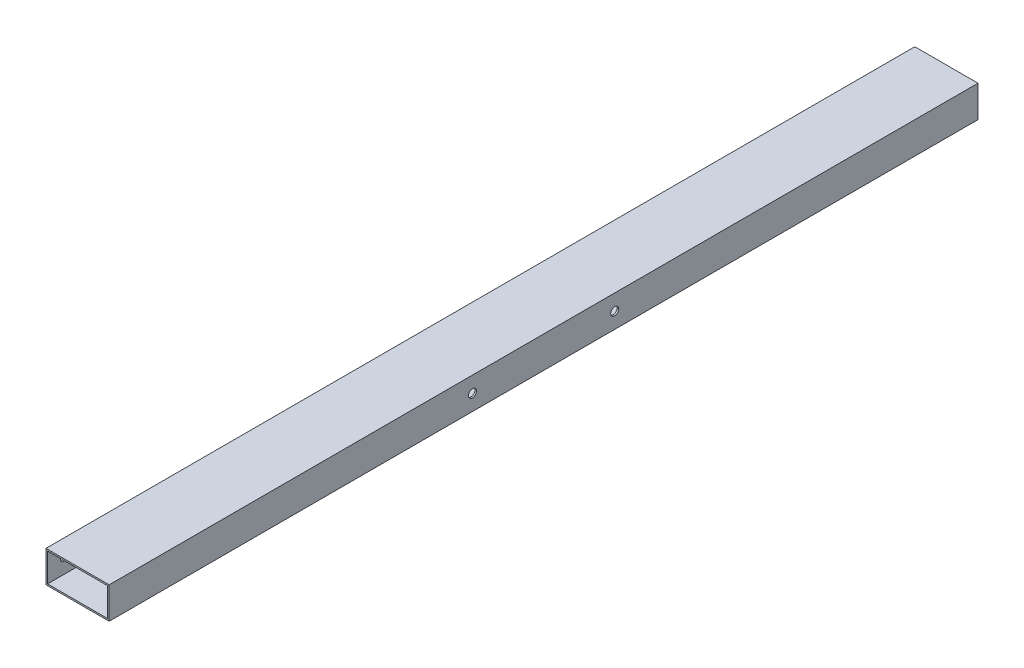
SolidWorks part; units mm, degrees
material "1060 合金"
ref_plane "前视基准面" through (0, 0, 0) normal (0, 0, 1) x (1, 0, 0)
ref_plane "上视基准面" through (0, 0, 0) normal (0, 1, 0) x (1, 0, 0)
ref_plane "右视基准面" through (0, 0, 0) normal (1, 0, 0) x (0, 0, -1)
other "Configuration Table"
sketch "草图1" plane through (0, 0, 0) normal (0, 0, 1) x (1, 0, 0)
  line L1 (0, 0) -> (40, 0)
  line L2 (0, 0) -> (0, -20)
  line L3 (0, -20) -> (40, -20)
  line L4 (40, 0) -> (40, -20)
  dimension "D1" = 20
  dimension "D2" = 40
extrude "拉伸-薄壁1" add sketch "草图1" along normal blind 550 thin
sketch "草图4" plane through (0, 0, 0) normal (-1, 0, 0) x (0, 0, 1)
  line L0 (550, 0) -> (0, 0) construction
  line L1 (550, 0) -> (550, -20) construction
  line L4 (0, -180.2783) -> (0, 689.7217) construction
  circle A1 centre (539.9964, -10) radius 1.75
  circle A49 centre (10, -10) radius 1.75
  dimension "D27" = 3.5
  dimension "D28" = 3.5
  dimension "D29" = 10
  dimension "D25" = 10
  dimension "D26" = 10.0036
  dimension "D30" = 10
extrude "切除-拉伸2" cut sketch "草图4" against normal blind 1.5
sketch "草图5" plane through (0, 0, 0) normal (-1, 0, 0) x (0, 0, 1)
  circle A0 centre (42.5, -10) radius 1.75 construction
  circle A1 centre (42.5, -10) radius 1.75
  circle A2 centre (62.5, -10) radius 1.75
  circle A3 centre (82.5, -10) radius 1.75
  circle A4 centre (102.5, -10) radius 1.75
  circle A5 centre (122.5, -10) radius 1.75
  circle A6 centre (142.5, -10) radius 1.75
  circle A7 centre (162.5, -10) radius 1.75
  circle A8 centre (182.5, -10) radius 1.75
  circle A9 centre (202.5, -10) radius 1.75
  circle A10 centre (222.5, -10) radius 1.75
  circle A11 centre (242.5, -10) radius 1.75
  circle A12 centre (262.5, -10) radius 1.75
  circle A13 centre (282.5, -10) radius 1.75
  circle A14 centre (302.5, -10) radius 1.75
  circle A15 centre (322.5, -10) radius 1.75
  circle A16 centre (342.5, -10) radius 1.75
  circle A17 centre (362.5, -10) radius 1.75
  circle A18 centre (382.5, -10) radius 1.75
  circle A19 centre (402.5, -10) radius 1.75
  circle A20 centre (422.5, -10) radius 1.75
  circle A21 centre (442.5, -10) radius 1.75
  circle A22 centre (462.5, -10) radius 1.75
  circle A23 centre (482.5, -10) radius 1.75
  dimension "D1" = 23
sketch "草图6" plane through (40, 0, 0) normal (1, 0, 0) x (0, 0, -1)
  line L0 (-550, -20) -> (0, -20) construction
  line L1 (-550, -20) -> (-550, 0) construction
  circle A0 centre (-320, -10) radius 2.5
  circle A1 centre (-230, -10) radius 2.5
  dimension "D1" = 5
  dimension "D2" = 5
  dimension "D3" = 10
  dimension "D4" = 10
  dimension "D5" = 230
  dimension "D6" = 230
extrude "切除-拉伸3" cut sketch "草图6" against normal through all
sketch "草图7" plane through (0, 0, 0) normal (-1, 0, 0) x (0, 0, 1)
  line L0 (550, -20) -> (0, -20) construction
  line L1 (0, 0) -> (0, -20) construction
  circle A0 centre (190, -10) radius 1.6
  circle A1 centre (170, -10) radius 1.6
  dimension "D1" = 3.2
  dimension "D2" = 3.2
  dimension "D3" = 10
  dimension "D4" = 10
  dimension "D5" = 170
  dimension "D6" = 20
extrude "切除-拉伸4" cut sketch "草图7" against normal blind 10
